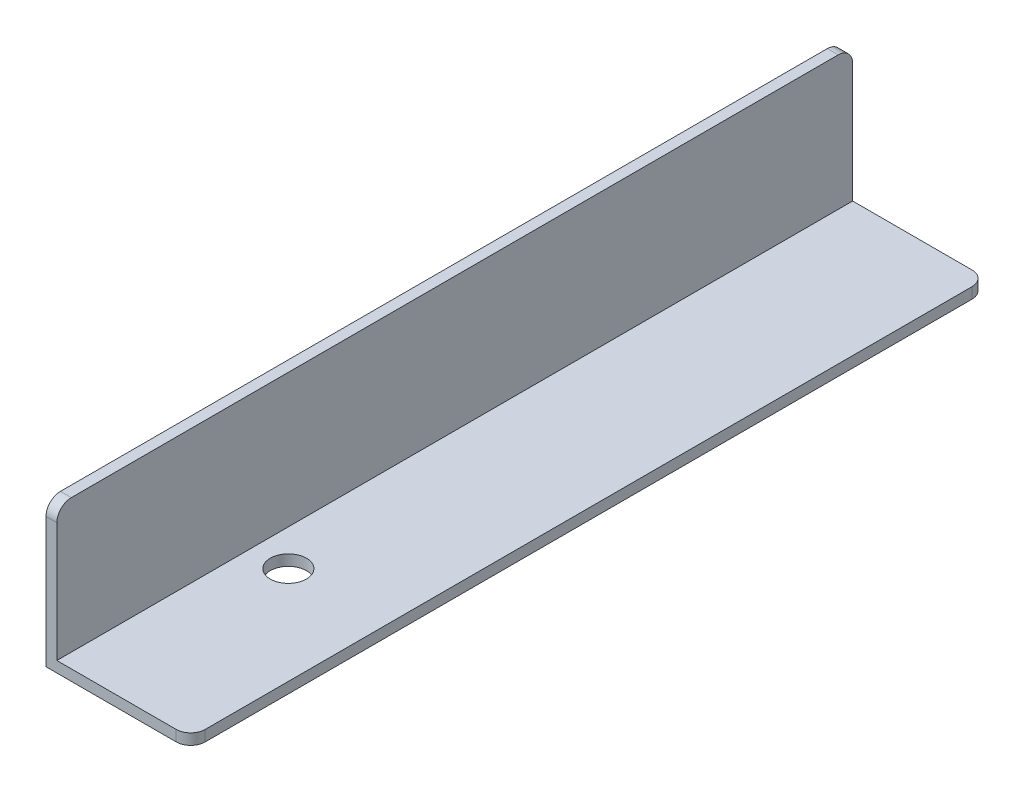
SolidWorks part; units mm, degrees
material "3.0205 (EN AW-1200)"
ref_plane "Ebene vorne" through (0, 0, 0) normal (0, 0, 1) x (1, 0, 0)
ref_plane "Ebene oben" through (0, 0, 0) normal (0, 1, 0) x (1, 0, 0)
ref_plane "Ebene rechts" through (0, 0, 0) normal (1, 0, 0) x (0, 0, -1)
sketch "Skizze1" plane through (0, 0, 0) normal (0, 0, 1) x (1, 0, 0)
  line L0 (0, 20) -> (0, 0)
  line L1 (0, 0) -> (20, 0)
  dimension "D1" = 20
extrude "Linear-Austragen-Dünn1" add sketch "Skizze1" against normal blind 110 thin thin type one direction reverse wall 1.5
sketch "Skizze2" plane through (0, 0, 0) normal (0, -1, 0) x (1, 0, 0)
  line L0 (1.5, -110) -> (1.5, 0) construction
  line L1 (0, 0) -> (20, 0) construction
  circle A0 centre (6.5, -27) radius 2.5
  dimension "D1" = 5
  dimension "D3" = 27
  dimension "D2" = 5
extrude "Schnitt-Linear austragen1" cut sketch "Skizze2" against normal blind 17
fillet "Verrundung1" radius 2 4 edges at (0.75, 20, -110) (20, 0.75, -110) (20, 0.75, 0) (0.75, 20, 0)
